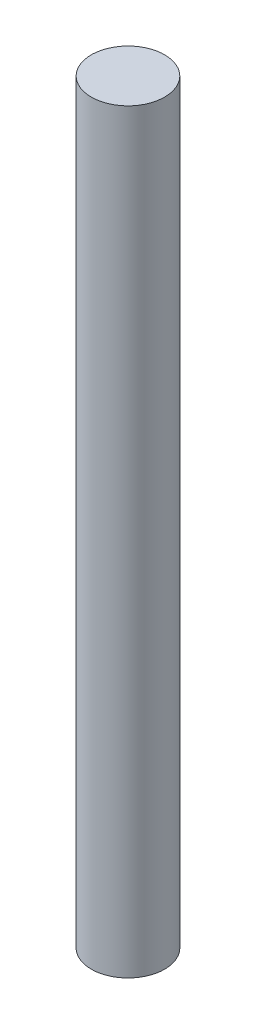
SolidWorks part; units mm, degrees
ref_plane "Front Plane" through (0, 0, 0) normal (0, 0, 1) x (1, 0, 0)
ref_plane "Top Plane" through (0, 0, 0) normal (0, 1, 0) x (1, 0, 0)
ref_plane "Right Plane" through (0, 0, 0) normal (1, 0, 0) x (0, 0, -1)
sketch "Sketch1" plane through (0, 0, 0) normal (0, 1, 0) x (1, 0, 0)
  circle A0 centre (0, 0) radius 15
  dimension "D1" = 30
extrude "Boss-Extrude1" add sketch "Sketch1" along normal blind 309
